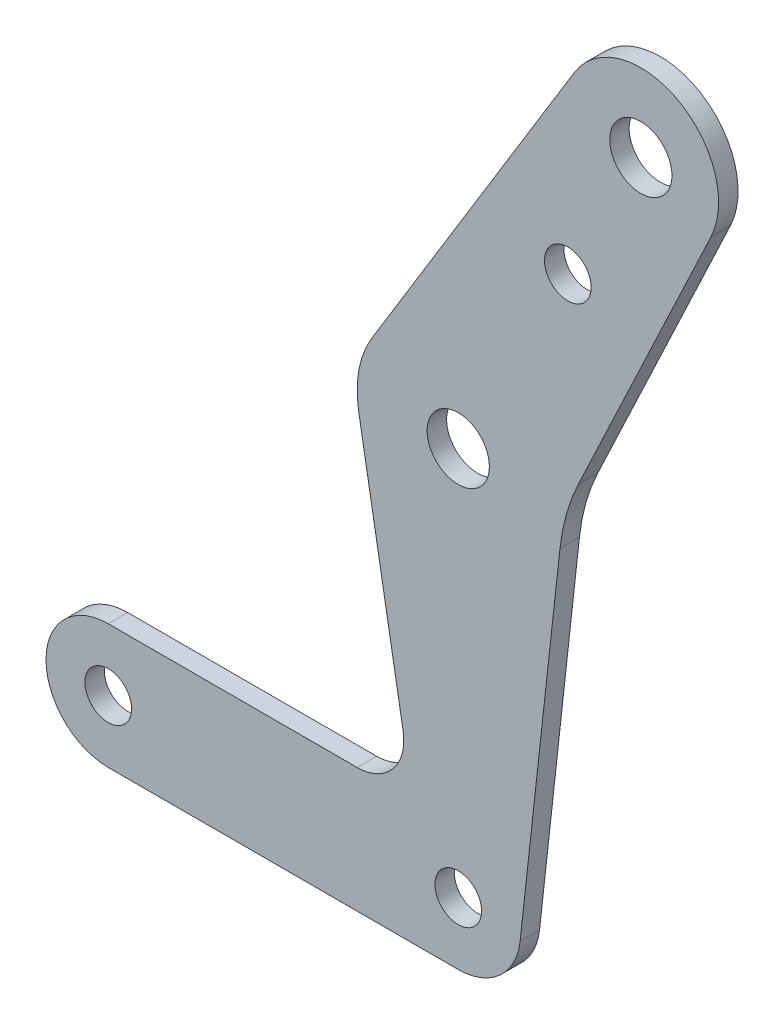
SolidWorks part; units mm, degrees
ref_plane "Front Plane" through (0, 0, 0) normal (0, 0, 1) x (1, 0, 0)
ref_plane "Top Plane" through (0, 0, 0) normal (0, 1, 0) x (1, 0, 0)
ref_plane "Right Plane" through (0, 0, 0) normal (1, 0, 0) x (0, 0, -1)
sketch "Sketch1" plane through (0, 0, 0) normal (0, 0, 1) x (1, 0, 0)
  line L0 (0, 0) -> (45, 0) construction
  line L1 (0, 8) -> (32, 8)
  line L2 (0, -8) -> (45, -8)
  line L3 (45, 0) -> (45, 50000) construction
  line L4 (45, 50) -> (68.4736, 94.1474) construction
  line L5 (68.4736, 94.1474) -> (45, 0) construction
  line L6 (59.9417, 99.3634) -> (33.9085, 56.7808)
  line L7 (32.1939, 47.7633) -> (37.9105, 15.0323)
  line L8 (77.5142, 89.8734) -> (60.4184, 53.7108)
  line L9 (58.0819, 45.4596) -> (52.9514, -0.8803)
  line L10 (45, 50) -> (-49074.8574, 9390.2145) construction
  arc A0 (0, 8) -> (0, -8) centre (0, 0) ccw
  arc A1 (45, -8) -> (52.9514, -0.8803) centre (45, 0) ccw
  circle A2 centre (0, 0) radius 3
  circle A3 centre (45, 0) radius 3
  circle A4 centre (45, 50) radius 4
  circle A5 centre (59.0841, 76.4884) radius 3
  circle A6 centre (68.4736, 94.1474) radius 4
  arc A7 (77.5142, 89.8734) -> (59.9417, 99.3634) centre (68.4736, 94.1474) ccw
  arc A8 (37.9105, 15.0323) -> (32, 8) centre (32, 14) cw
  arc A9 (33.9085, 56.7808) -> (32.1939, 47.7633) centre (45, 50) ccw
  arc A10 (60.4184, 53.7108) -> (58.0819, 45.4596) centre (83.924, 42.5985) ccw
  point P46 (32.2288, 52.4285)
  dimension "D1" = 6
  dimension "D2" = 6
  dimension "D4" = 8
  dimension "D5" = 8
  dimension "D6" = 6
  dimension "D7" = 8
  dimension "D12" = 20
  dimension "D13" = 6
  dimension "D14" = 13
  dimension "D15" = 26
  dimension "D3" = 45
  dimension "D8" = 20
  dimension "D9" = 50
  dimension "D10" = 50
  dimension "D11" = 14
  dimension "D16" = 32
  dimension "D17" = 40
extrude "Boss-Extrude1" add sketch "Sketch1" along normal blind 2.5
